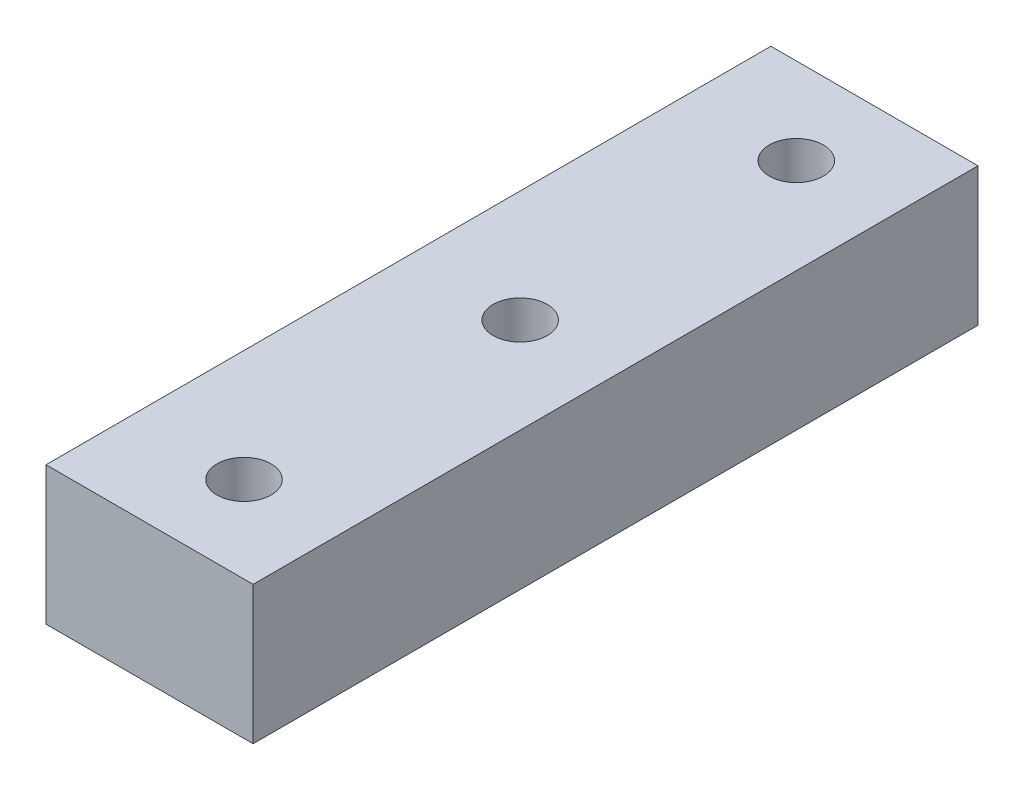
SolidWorks part; units mm, degrees
material "6061 Alloy"
ref_plane "Front Plane" through (0, 0, 0) normal (0, 0, 1) x (1, 0, 0)
ref_plane "Top Plane" through (0, 0, 0) normal (0, 1, 0) x (1, 0, 0)
ref_plane "Right Plane" through (0, 0, 0) normal (1, 0, 0) x (0, 0, -1)
sketch "Sketch4" plane through (0, 0, 0) normal (0, 1, 0) x (1, 0, 0)
  line L8 (-61.3338, 18.9329) -> (-61.3338, -6.4671) construction
  line L9 (-61.3338, 6.2329) -> (-71.6088, 6.2329) construction
  line L10 (-71.6088, -0.9671) -> (-71.6088, 13.4329) construction
  line L11 (-71.6088, 6.2329) -> (-71.6088, 28.4579)
  line L12 (-71.6088, 28.4579) -> (-52.5588, 28.4579)
  line L13 (-52.5588, 28.4579) -> (-52.5588, -12.8171)
  line L15 (-71.6088, -12.8171) -> (-71.6088, 6.2329)
  line L16 (-52.5588, -12.8171) -> (-52.5588, -38.2171)
  line L17 (-71.6088, -12.8171) -> (-71.6088, -38.2171)
  line L18 (-71.6088, -38.2171) -> (-52.5588, -38.2171)
  dimension "D1" = 66.675
extrude "Boss-Extrude1" add sketch "Sketch4" along normal blind 12.7
sketch "Sketch5" plane through (0, 12.7, 0) normal (0, 1, 0) x (1, 0, 0)
  line L0 (-61.3338, -4.8796) -> (-61.3338, -30.2796) construction
  line L1 (-52.5588, -4.8796) -> (-61.3338, -4.8796) construction
  line L2 (-52.5588, -38.2171) -> (-52.5588, 28.4579) construction
  line L3 (-61.3338, 20.5204) -> (-61.3338, -4.8796) construction
  dimension "D1" = 0
hole_wizard "#10 Clearance Hole1" positions "Sketch6" profile "Sketch7" hole size "#10" standard "ANSI Inch" end condition through all
sketch "Sketch6" plane through (0, 12.7, 0) normal (0, 1, 0) x (1, 0, 0)
  point P0 (-61.3338, 20.5204)
  point P3 (-61.3338, -4.8796)
  point P6 (-61.3338, -30.2796)
sketch "Sketch7" plane through (-61.3338, 12.7, -20.5204) normal (1, 0, 0) x (0, 0, 1)
  line L0 (0, 0) -> (0, 12.7)
  line L1 (0, 12.7) -> (2.4892, 12.7)
  line L2 (2.4892, 12.7) -> (2.4892, 0)
  line L5 (2.4892, 0) -> (0, 0)
  line L11 (0, -6.35) -> (0, 107.95) construction
  dimension "Thru Hole Dia." = 4.9784
  dimension "Thru Hole Depth" = 12.7
